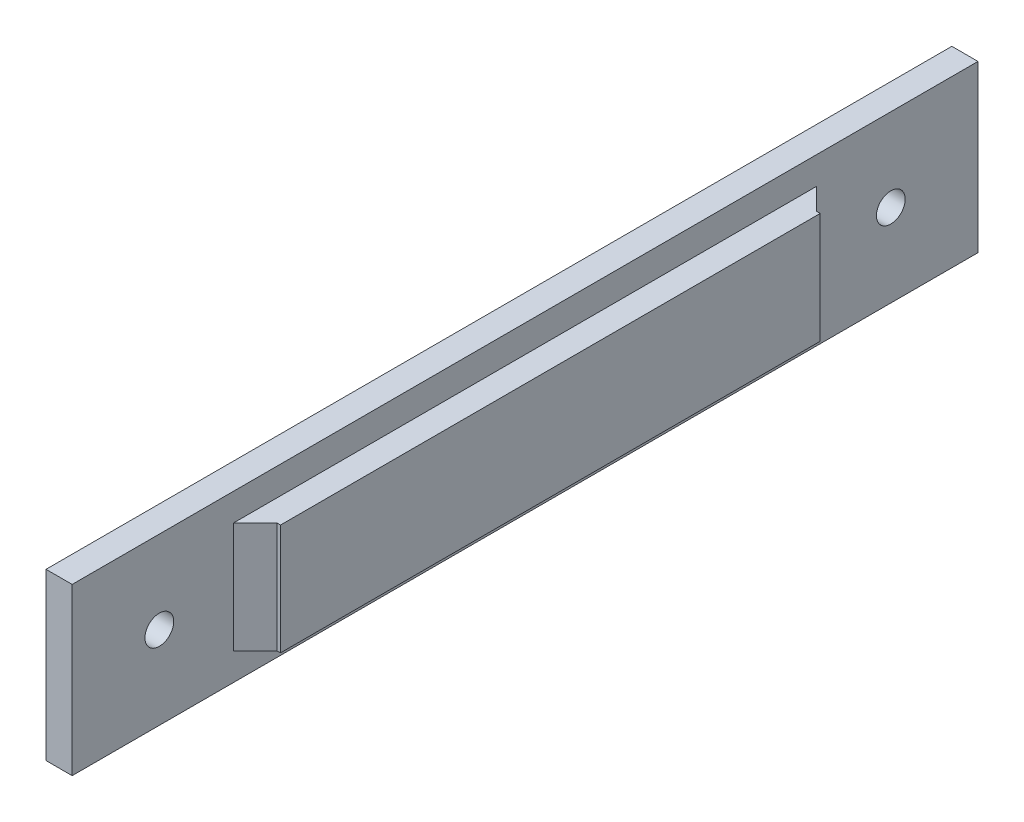
SolidWorks part; units mm, degrees
ref_plane "前视基准面" through (0, 0, 0) normal (0, 0, 1) x (1, 0, 0)
ref_plane "上视基准面" through (0, 0, 0) normal (0, 1, 0) x (1, 0, 0)
ref_plane "右视基准面" through (0, 0, 0) normal (1, 0, 0) x (0, 0, -1)
sketch "草图1" plane through (0, 0, 0) normal (0, 0, 1) x (1, 0, 0)
  line L1 (0, 0) -> (13, 0)
  line L2 (0, 0) -> (0, 13)
  line L3 (0, 13) -> (13, 13)
  line L4 (13, 0) -> (13, 13)
  dimension "D1" = 13
  dimension "D2" = 13
extrude "拉伸-薄壁1" add sketch "草图1" along normal blind 103.9 thin
sketch "草图2" plane through (-3, 0, 0) normal (-1, 0, 0) x (0, 0, 1)
  line L0 (0, 16) -> (0, -3) construction
  line L1 (103.9, 16) -> (103.9, -3) construction
  circle A0 centre (10, 6.5) radius 1.65
  circle A1 centre (93.9, 6.5) radius 1.65
  dimension "D1" = 3.3
  dimension "D2" = 3.3
  dimension "D3" = 10
  dimension "D4" = 10
extrude "切除-拉伸1" cut sketch "草图2" against normal blind 30
sketch "草图3" plane through (16, 0, 0) normal (1, 0, 0) x (0, 0, -1)
  line L1 (-103.9, 16) -> (0, 16)
  line L2 (-103.9, 16) -> (-103.9, -3)
  line L3 (-103.9, -3) -> (0, -3)
  line L4 (0, 16) -> (0, -3)
extrude "切除-拉伸2" cut sketch "草图3" against normal blind 16
sketch "草图4" plane through (0, 0, 0) normal (1, 0, 0) x (0, 0, -1)
  line L0 (0, 16) -> (0, -3) construction
  line L1 (-82.9, 12.85) -> (-21, 12.85)
  line L2 (-82.9, 12.85) -> (-82.9, 0.15)
  line L3 (-82.9, 0.15) -> (-21, 0.15)
  line L4 (-21, 12.85) -> (-21, 0.15)
  line L5 (-103.9, 16) -> (-103.9, -3) construction
  line L6 (-103.9, -3) -> (0, -3) construction
  line L7 (0, 16) -> (-103.9, 16) construction
  point P8 (-21, 6.5)
  dimension "D1" = 21
  dimension "D2" = 21
  dimension "D3" = 12.7
  dimension "D4" = 9.5
  dimension "D5" = 3.15
  dimension "D6" = 3.15
extrude "凸台-拉伸1" add sketch "草图4" along normal blind 2.9
chamfer "倒角1" distance 2.5 angle 45 2 edges at (0, 6.5, 21) (0, 6.5, 82.9)
